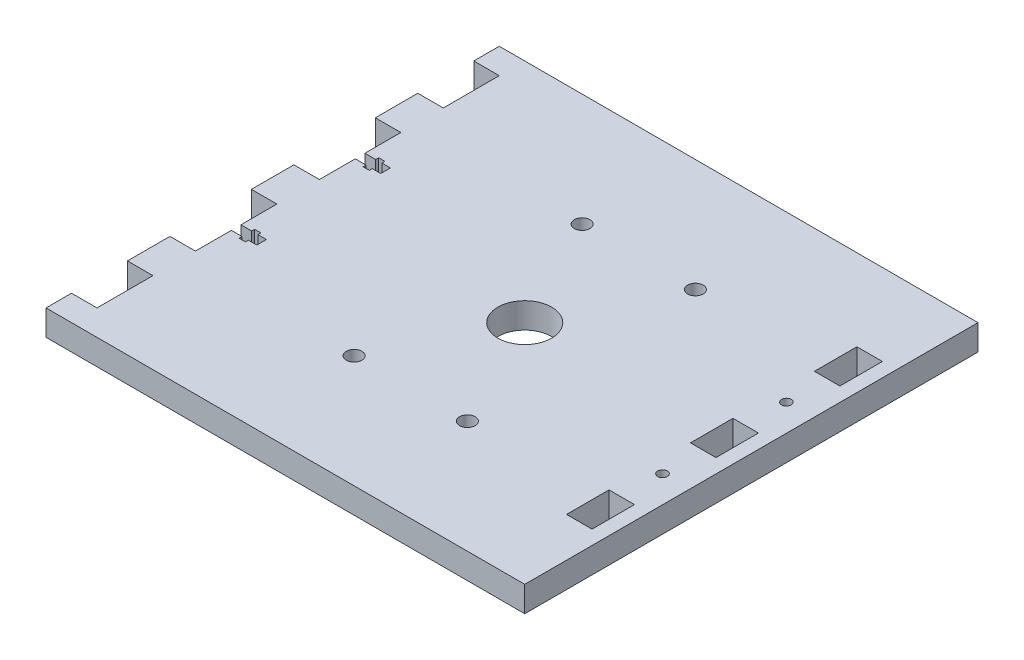
SolidWorks part; units mm, degrees
ref_plane "Front Plane" through (0, 0, 0) normal (0, 0, 1) x (1, 0, 0)
ref_plane "Top Plane" through (0, 0, 0) normal (0, 1, 0) x (1, 0, 0)
ref_plane "Right Plane" through (0, 0, 0) normal (1, 0, 0) x (0, 0, -1)
sketch "Sketch1" plane through (0, 0, 0) normal (0, 1, 0) x (1, 0, 0)
  line L1 (80, -80) -> (-80, -80)
  line L2 (80, -80) -> (80, 80)
  line L3 (80, 80) -> (-80, 80)
  line L4 (-80, -80) -> (-80, 80)
  line L5 (80, -80) -> (-80, 80) construction
  line L6 (80, 80) -> (-80, -80) construction
  point P0 (0, 0)
  dimension "D1" = 160
extrude "Boss-Extrude1" add sketch "Sketch1" along normal blind 9
sketch "Sketch2" plane through (0, 9, 0) normal (0, 1, 0) x (1, 0, 0)
  line L0 (-80, 80) -> (-80, -80) construction
  line L1 (-80, -7.5) -> (-89, -7.5)
  line L2 (-80, -7.5) -> (-80, 7.5)
  line L3 (-80, 7.5) -> (-89, 7.5)
  line L4 (-89, -7.5) -> (-89, 7.5)
  line L5 (-80, 0) -> (0, 0) construction
  line L6 (-80, 80) -> (-80, 51.25) construction
  line L7 (-80, 51.25) -> (-89, 51.25)
  line L8 (-80, 51.25) -> (-80, 36.25)
  line L9 (-80, 36.25) -> (-89, 36.25)
  line L10 (-89, 51.25) -> (-89, 36.25)
  line L11 (-80, -36.25) -> (-89, -36.25)
  line L12 (-80, -36.25) -> (-80, -51.25)
  line L13 (-80, -51.25) -> (-89, -51.25)
  line L14 (-89, -36.25) -> (-89, -51.25)
  line L15 (-80, 36.25) -> (-80, 7.5) construction
  line L16 (-80, -7.5) -> (-80, -36.25) construction
  line L17 (-80, -51.25) -> (-80, -80) construction
  line L19 (-80, 80) -> (-89, 80)
  line L20 (-80, 80) -> (-80, 71)
  line L21 (-80, 71) -> (-89, 71)
  line L22 (-89, 80) -> (-89, 71)
  line L23 (-80, -80) -> (-89, -80)
  line L24 (-80, -80) -> (-80, -71)
  line L25 (-80, -71) -> (-89, -71)
  line L26 (-89, -80) -> (-89, -71)
  dimension "D1" = 9
  dimension "D2" = 15
  dimension "D3" = 9
extrude "Boss-Extrude2" add sketch "Sketch2" against normal up to surface (9 mm away) up to face at (0, 0, 0)
sketch "Sketch3" plane through (0, 9, 0) normal (0, 1, 0) x (1, 0, 0)
  line L1 (75, 51.25) -> (66, 51.25)
  line L2 (75, 51.25) -> (75, 36.25)
  line L3 (75, 36.25) -> (66, 36.25)
  line L4 (66, 51.25) -> (66, 36.25)
  line L5 (-80, 51.25) -> (-89, 51.25) construction
  line L6 (75, 7.5) -> (66, 7.5)
  line L7 (75, 7.5) -> (75, -7.5)
  line L8 (75, -7.5) -> (66, -7.5)
  line L9 (66, 7.5) -> (66, -7.5)
  line L10 (75, -36.25) -> (66, -36.25)
  line L11 (75, -36.25) -> (75, -51.25)
  line L12 (75, -51.25) -> (66, -51.25)
  line L13 (66, -36.25) -> (66, -51.25)
  line L14 (-80, 7.5) -> (-89, 7.5) construction
  line L15 (-89, -7.5) -> (-80, -7.5) construction
  line L16 (-89, -51.25) -> (-80, -51.25) construction
  line L17 (80, -80) -> (80, 80) construction
  line L18 (70.5, 36.25) -> (70.5, 7.5) construction
  line L19 (70.5, 7.5) -> (70.5, -7.5) construction
  line L20 (70.5, -7.5) -> (70.5, -36.25) construction
  line L21 (70.5, -36.25) -> (70.5, -51.25) construction
  line L22 (70.5, -51.25) -> (70.5, -80) construction
  line L23 (-89, -80) -> (80, -80) construction
  line L24 (70.5, 51.25) -> (70.5, 80) construction
  line L25 (80, 80) -> (-89, 80) construction
  circle A0 centre (70.5, 21.875) radius 1.7
  circle A1 centre (70.5, -21.875) radius 1.7
  dimension "D2" = 3.4
  dimension "D1" = 5
extrude "Cut-Extrude1" cut sketch "Sketch3" against normal through all
sketch "Sketch4" plane through (0, 9, 0) normal (0, 1, 0) x (1, 0, 0)
  line L1 (-80, 36.25) -> (-80, 7.5) construction
  line L2 (-89, 51.25) -> (-89, 36.25) construction
  line L3 (-89, 0) -> (0, 0) construction
  line L4 (-89, 7.5) -> (-89, -7.5) construction
  line L5 (-80, -21.875) -> (-71, -21.875) construction
  line L6 (-80, 23.575) -> (-76.2, 23.575)
  line L7 (-80, -23.575) -> (-80, -20.175)
  line L8 (-76.2, -20.175) -> (-80, -20.175)
  line L9 (-76.2, -19.125) -> (-76.2, -20.175)
  line L10 (-74, -19.125) -> (-76.2, -19.125)
  line L11 (-74, -20.175) -> (-74, -19.125)
  line L12 (-71, -20.175) -> (-74, -20.175)
  line L13 (-71, -23.575) -> (-71, -20.175)
  line L14 (-74, -23.575) -> (-71, -23.575)
  line L15 (-74, -24.625) -> (-74, -23.575)
  line L16 (-76.2, -24.625) -> (-74, -24.625)
  line L17 (-76.2, -23.575) -> (-76.2, -24.625)
  line L18 (-80, -23.575) -> (-76.2, -23.575)
  line L20 (-76.2, 23.575) -> (-76.2, 24.625)
  line L21 (-76.2, 24.625) -> (-74, 24.625)
  line L22 (-74, 24.625) -> (-74, 23.575)
  line L23 (-74, 23.575) -> (-71, 23.575)
  line L24 (-71, 23.575) -> (-71, 20.175)
  line L25 (-71, 20.175) -> (-74, 20.175)
  line L26 (-74, 20.175) -> (-74, 19.125)
  line L27 (-74, 19.125) -> (-76.2, 19.125)
  line L28 (-76.2, 19.125) -> (-76.2, 20.175)
  line L29 (-76.2, 20.175) -> (-80, 20.175)
  line L30 (-80, 23.575) -> (-80, 20.175)
  line L31 (-80, 21.875) -> (-71, 21.875) construction
  dimension "D1" = 3.4
  dimension "D2" = 18
  dimension "D3" = 2.2
  dimension "D4" = 5.5
  dimension "D5" = 3
extrude "Cut-Extrude2" cut sketch "Sketch4" against normal through all
sketch "Sketch5" plane through (0, 9, 0) normal (0, 1, 0) x (1, 0, 0)
  line L0 (-22.75, 40.25) -> (-22.75, -40.25) construction
  line L5 (20, -40.25) -> (-20, 40.25) construction
  line L6 (20, 40.25) -> (-20, -40.25) construction
  line L7 (-20, 43) -> (20, 43) construction
  line L8 (22.75, 40.25) -> (22.75, -40.25) construction
  line L9 (-20, -43) -> (20, -43) construction
  circle A0 centre (0, 0) radius 9.5
  circle A1 centre (-20, 40.25) radius 2.75
  circle A2 centre (20, 40.25) radius 2.75
  circle A3 centre (20, -40.25) radius 2.75
  circle A4 centre (-20, -40.25) radius 2.75
  dimension "D1" = 19
  dimension "D2" = 5.5
  dimension "D3" = 45.5
  dimension "D4" = 86
extrude "Cut-Extrude3" cut sketch "Sketch5" against normal through all
